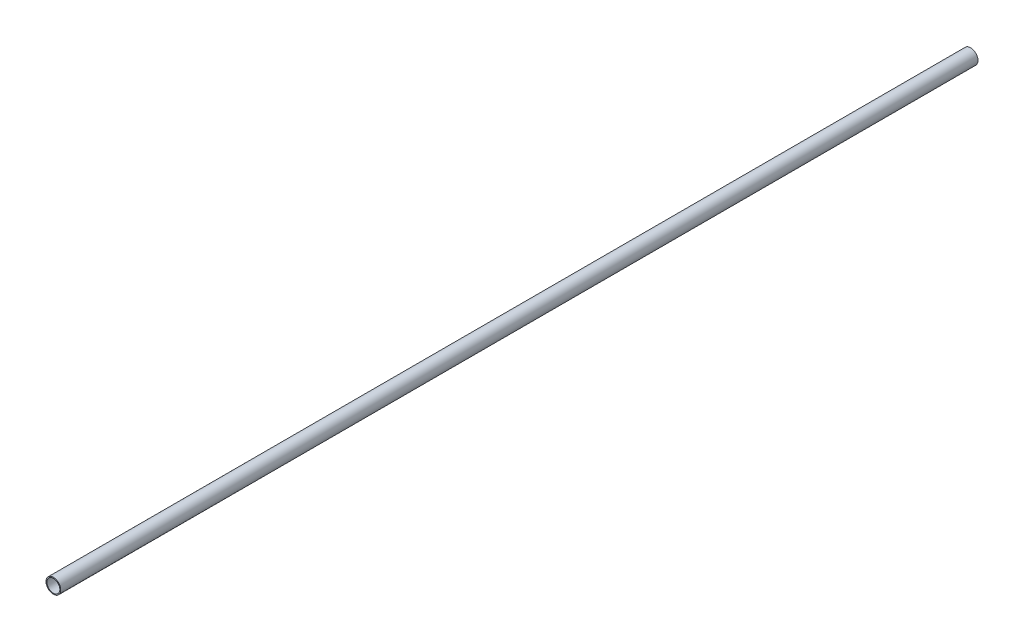
SolidWorks part; units mm, degrees
ref_plane "Plano frontal" through (0, 0, 0) normal (0, 0, 1) x (1, 0, 0)
ref_plane "Plano superior" through (0, 0, 0) normal (0, 1, 0) x (1, 0, 0)
ref_plane "Plano direito" through (0, 0, 0) normal (1, 0, 0) x (0, 0, -1)
sketch "Sketch2" plane through (0, 0, 0) normal (0, 0, 1) x (1, 0, 0)
  circle A0 centre (2449.7201, -5187.0074) radius 24.125
  circle A1 centre (2449.7201, -5187.0074) radius 21.075
  dimension "D1" = 3.05
extrude "Boss-Extrude1" add sketch "Sketch2" along normal blind 3000
